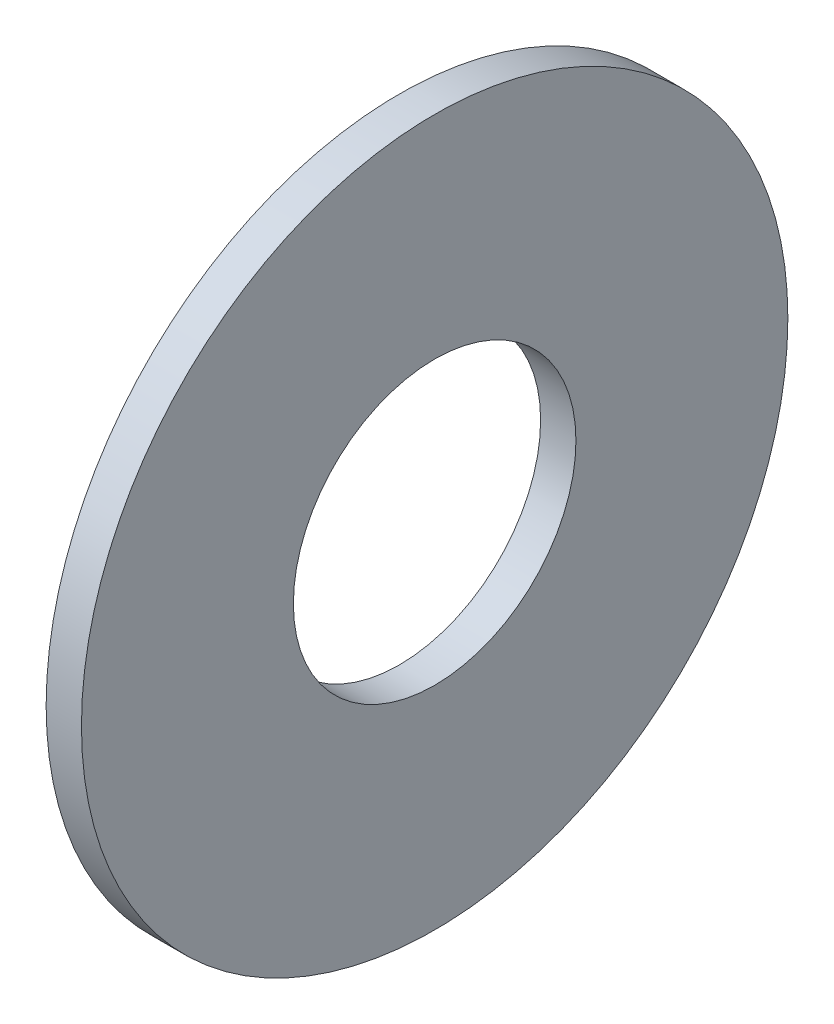
SolidWorks part; units mm, degrees
ref_plane "Front Plane" through (0, 0, 0) normal (0, 0, 1) x (1, 0, 0)
ref_plane "Top Plane" through (0, 0, 0) normal (0, 1, 0) x (1, 0, 0)
ref_plane "Right Plane" through (0, 0, 0) normal (1, 0, 0) x (0, 0, -1)
sketch "Sketch2" plane through (0, 0, 0) normal (1, 0, 0) x (0, 0, -1)
  circle A0 centre (0, 0) radius 10
  circle A1 centre (0, 0) radius 4
  dimension "D1" = 20
  dimension "D2" = 8
extrude "Boss-Extrude1" add sketch "Sketch2" along normal blind 1
